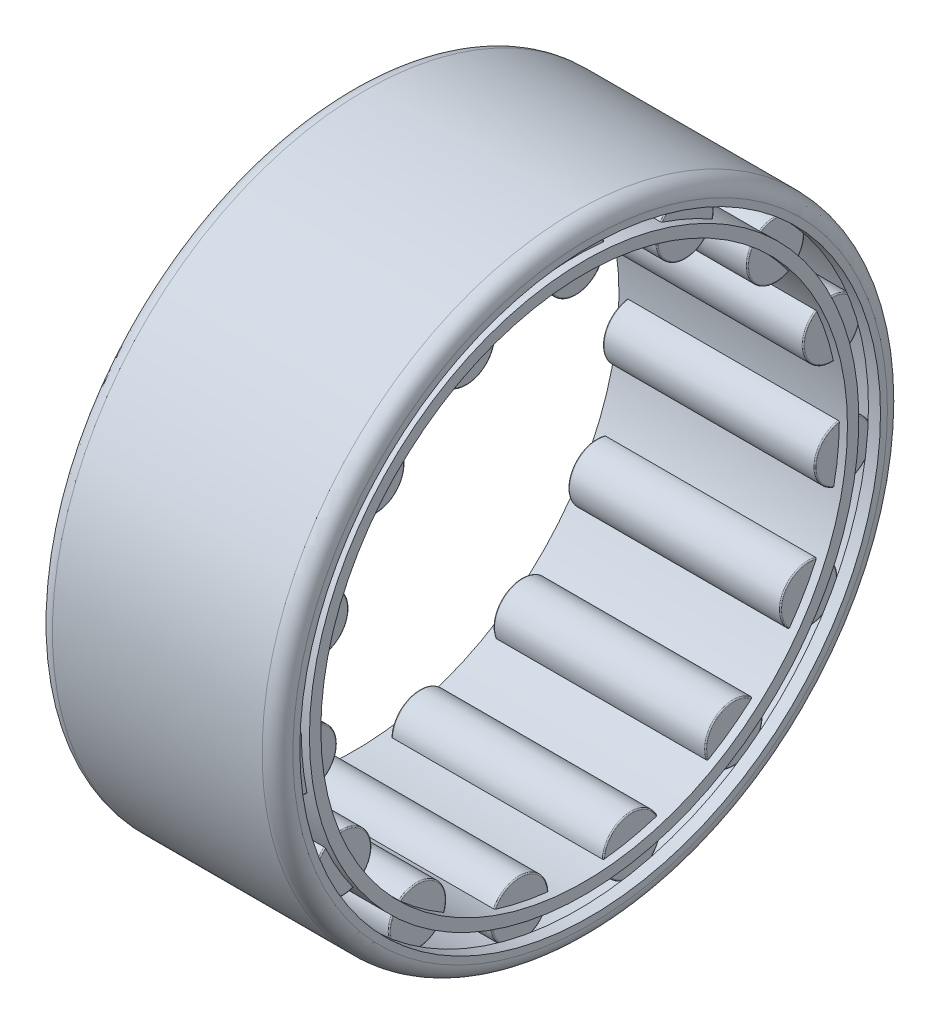
SolidWorks part; units mm, degrees
ref_plane "Plane1" through (0, 0, 0) normal (0, 0, 1) x (1, 0, 0)
ref_plane "Plane2" through (0, 0, 0) normal (0, 1, 0) x (1, 0, 0)
ref_plane "Plane3" through (0, 0, 0) normal (1, 0, 0) x (0, 0, -1)
sketch "Clipboard" plane through (0, 0, 0) normal (0, 0, 1) x (1, 0, 0)
  line L0 (-10, 0) -> (10, 0) construction
  line L1 (41.1529, 1.4371) -> (62.7517, -4.3503)
  line L2 (41.1529, 1.4371) -> (75.4583, 10.6292)
  line L3 (41.1529, 1.4371) -> (62.7517, -4.3503)
  line L4 (41.1529, 1.4371) -> (-22.3471, -0.7804)
  dimension "Count" = 15
  dimension "Show_count" = 15
  dimension "Max_count" = 15
sketch "InnRacSke" plane through (0, 0, 0) normal (0, 0, 1) x (1, 0, 0)
  line L0 (-14.2875, 38.3286) -> (-15.875, 38.3286)
  line L1 (-15.875, 38.3286) -> (-15.875, 39.243)
  line L2 (-13.843, 41.275) -> (13.843, 41.275)
  line L4 (15.875, 39.243) -> (15.875, 38.3286)
  line L5 (15.875, 38.3286) -> (14.2875, 38.3286)
  line L6 (14.2875, 38.3286) -> (14.2875, 39.2811)
  line L7 (14.2875, 39.2811) -> (-14.2875, 39.2811)
  line L8 (-14.2875, 39.2811) -> (-14.2875, 38.3286)
  line L9 (-31.75, 0) -> (31.75, 0) construction
  arc A0 (-15.875, 39.243) -> (-13.843, 41.275) centre (-13.843, 39.243) cw
  arc A2 (13.843, 41.275) -> (15.875, 39.243) centre (13.843, 39.243) cw
revolve "Race" add sketch "InnRacSke" angle 360 about L9
sketch "RolDetSke" plane through (0, 0, 0) normal (0, 0, 1) x (1, 0, 0)
  line L0 (-14.0018, 39.131) -> (-14.0017, 35.5155)
  line L1 (-14.0017, 35.5155) -> (14.0017, 35.5155)
  line L2 (14.0017, 35.5155) -> (14.0018, 39.131)
  line L3 (13.8511, 39.2816) -> (-13.8511, 39.2816)
  line L4 (-28.575, 35.5155) -> (28.575, 35.5155) construction
  arc A0 (14.0018, 39.131) -> (13.8511, 39.2816) centre (13.8511, 39.131) ccw
  arc A1 (-13.8511, 39.2816) -> (-14.0018, 39.131) centre (-13.8511, 39.131) ccw
revolve "RollerDetailed" add sketch "RolDetSke" angle 360 about L4
ref_axis "Axis1" through (-50, 0, 0) along (1, 0, 0)
sketch "CagSpiSke" plane through (0, 0, 0) normal (0, 0, 1) x (1, 0, 0)
  line L0 (15.0812, 34.7623) -> (15.0812, 36.2688)
  line L1 (15.0812, 36.2688) -> (-15.0813, 36.2688)
  line L2 (-15.0813, 36.2688) -> (-15.0813, 34.7623)
  line L3 (-15.0813, 34.7623) -> (15.0812, 34.7623)
  line L4 (-31.75, 0) -> (31.75, 0) construction
revolve "CageSpine" add sketch "CagSpiSke" angle 360 about L4
pattern_circular "RollersDetailed" count 15 every 24 about axis through (-50, 0, 0) along (1, 0, 0) of "RollerDetailed"
sketch "RolSimSke" plane through (0, 0, 0) normal (0, 0, 1) x (1, 0, 0)
  line L0 (-25.4, 0) -> (25.4, 0) construction
  line L2 (-13.8511, 39.2821) -> (13.8511, 39.2821)
  line L3 (-14.0018, 39.1315) -> (-14.0018, 31.9006)
  line L4 (-13.8511, 31.75) -> (13.8511, 31.75)
  line L5 (14.0017, 39.1315) -> (14.0017, 31.9006)
  arc A0 (-14.0018, 31.9006) -> (-13.8511, 31.75) centre (-13.8511, 31.9006) ccw
  arc A1 (-13.8511, 39.2821) -> (-14.0018, 39.1315) centre (-13.8511, 39.1315) ccw
  arc A2 (14.0017, 39.1315) -> (13.8511, 39.2821) centre (13.8511, 39.1315) ccw
  arc A3 (13.8511, 31.75) -> (14.0017, 31.9006) centre (13.8511, 31.9006) ccw
  point P10 (-14.0018, 31.75)
  point P15 (14.0017, 39.2821)
  point P18 (14.0017, 31.75)
revolve "RollersSimplified" [suppressed] add sketch "RolSimSke" angle 360 about L0
equation "\"BallCLRad@Clipboard\" =  ( \"D1@InnRacSke\" + \"Bore@Clipboard\" )  / 4"
equation "\"RollerCLRad@RolDetSke\" = \"BallCLRad@Clipboard\""
equation "\"halfCyl@InnRacSke\" = \"Cyl_Len@InnRacSke\" / 2"
equation "\"Roller_diameter@RolDetSke\" =  ( \"D1@InnRacSke\" - \"Bore@Clipboard\" )  / 2 + .001"
equation "\"Roller_radius@RolDetSke\" = \"Roller_diameter@RolDetSke\" / 50"
equation "\"Roller_length@RolDetSke\" = \"Cyl_Len@InnRacSke\" * .98"
equation "\"halfLength@RolDetSke\" = \"Roller_length@RolDetSke\" / 2"
equation "\"Cage_width@CagSpiSke\" =  ( \"Cyl_Len@InnRacSke\" + \"Width@InnRacSke\" )  / 2"
equation "\"halfWidth@CagSpiSke\" = \"Cage_width@CagSpiSke\" / 2"
equation "\"Roller_length@RolSimSke\" = \"Cyl_Len@InnRacSke\" * .98"
equation "\"halfWidth@RolSimSke\" = \"Roller_length@RolSimSke\" / 2"
equation "\"D1@RolSimSke\" = \"Roller_radius@RolDetSke\""
equation "\"Roller_diameter@RolSimSke\" =  ( \"D1@InnRacSke\" - \"Bore@Clipboard\" )  / 2 + .001"
equation "\"Cage_thickness@CagSpiSke\"  = \"Roller_diameter@RolDetSke\" / 5"
equation "\"D2@CagSpiSke\" =  \"RollerCLRad@RolDetSke\" * 2 - \"Cage_thickness@CagSpiSke\""
equation "\"Max_count@Clipboard\" = int( 3.14159265 / atn(( \"Roller_diameter@RolDetSke\" / 2) / sqr( \"RollerCLRad@RolDetSke\"  *  \"RollerCLRad@RolDetSke\" - ( \"Roller_diameter@RolDetSke\" / 2) *  ( \"Roller_diameter@RolDetSke\" / 2))))"
equation "\"Max_count@Clipboard\" = ((sgn( \"Max_count@Clipboard\" - \"Count@Clipboard\" )-1)*( \"Max_count@Clipboard\" - \"Count@Clipboard\" ))/-2+ \"Count@Clipboard\""
equation "\"Count@RollersDetailed\" = int( \"Show_count@Clipboard\" ) "
equation "\"Count@RollersDetailed\" = ((sgn( \"Count@RollersDetailed\" - \"Max_count@Clipboard\" )-1)*( \"Count@RollersDetailed\" - \"Max_count@Clipboard\" ))/-2+ \"Max_count@Clipboard\""
equation "\"Count@RollersDetailed\" = ((sgn( \"Count@RollersDetailed\" - \"Min_count@Clipboard\" )+1)*( \"Count@RollersDetailed\" - \"Min_count@Clipboard\"))/2 +\"Min_count@Clipboard\""
equation "\"Angle@RollersDetailed\" = 360.0 / \"Max_count@Clipboard\""
equation "\"Angle@CageSpine\" =  \"Angle@RollersDetailed\" * ( \"Count@RollersDetailed\" -1 + int( \"Count@RollersDetailed\" / \"Max_count@Clipboard\" ) )  + 0.001 -  int( \"Count@RollersDetailed\" / \"Max_count@Clipboard\" ) * 0.001"
equation "\"Angle@CageSpine\" =  \"Angle@CageSpine\" * int( \"Min_count@Clipboard\" / 2) + int(1 / \"Min_count@Clipboard\")  * 0.001"
equation "\"Bore@RolSimSke\" = \"Bore@Clipboard\""
